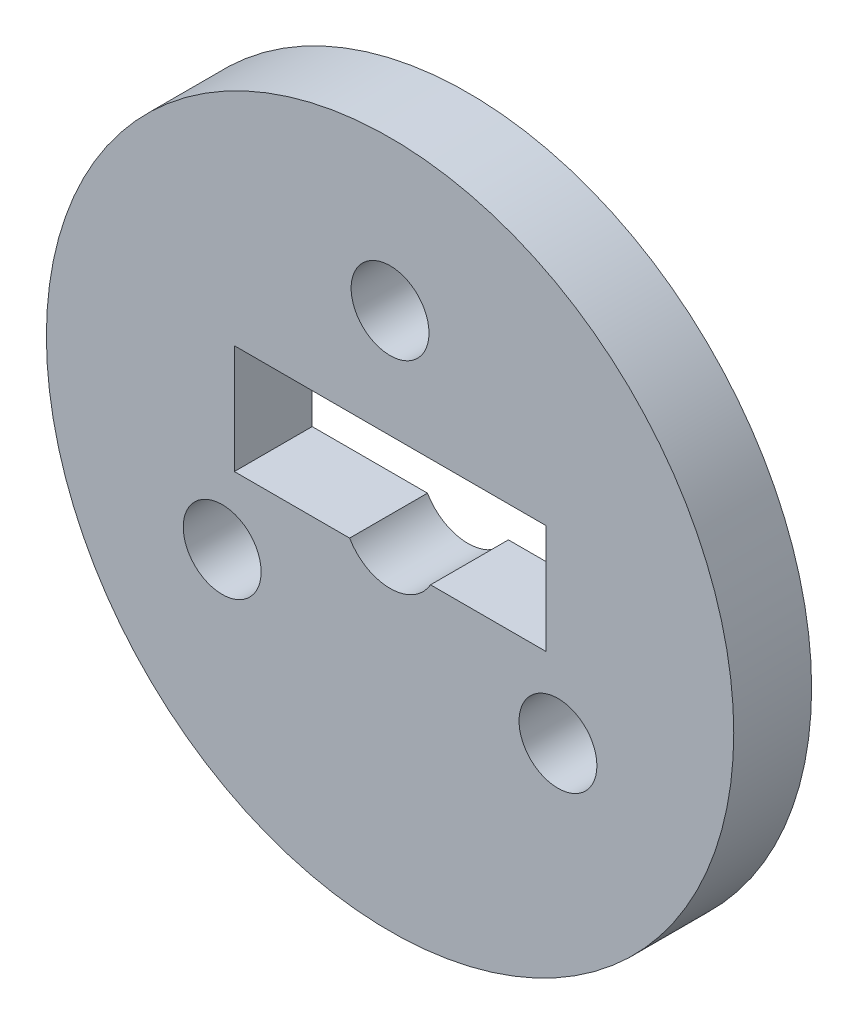
SolidWorks part; units mm, degrees
ref_plane "정면" through (0, 0, 0) normal (0, 0, 1) x (1, 0, 0)
ref_plane "윗면" through (0, 0, 0) normal (0, 1, 0) x (1, 0, 0)
ref_plane "우측면" through (0, 0, 0) normal (1, 0, 0) x (0, 0, -1)
sketch "스케치1" plane through (0, 0, 0) normal (0, 0, 1) x (1, 0, 0)
  line L0 (0, 0) -> (0, 33.5972) construction
  line L1 (0, 0) -> (0, 53.0624) construction
  line L6 (10, -1.5) -> (10, 5.5)
  line L7 (-10, 5.5) -> (-10, -1.5)
  line L8 (0, 0) -> (-11.0851, -6.4) construction
  line L9 (10, 5.5) -> (-10, 5.5)
  line L10 (10, -1.5) -> (-10, -1.5)
  line L11 (10, 5.5) -> (-10, -1.5) construction
  line L12 (10, -1.5) -> (-10, 5.5) construction
  circle A0 centre (0, 0) radius 22.0716
  circle A1 centre (0, 12.45) radius 2.5
  circle A2 centre (0, 0) radius 15.95
  circle A3 centre (10.782, -6.225) radius 2.5
  circle A4 centre (-10.782, -6.225) radius 2.5
  circle A6 centre (0, 0) radius 3
  point P0 (0, 2)
  point P14 (0, 0)
  point P22 (0, 0)
  dimension "D1" = 5
  dimension "D2" = 31.9
  dimension "D3" = 44.1433
  dimension "D4" = 12.45
  dimension "D6" = 2
  dimension "D7" = 20
  dimension "D9" = 6
  dimension "D8" = 7
  dimension "D5" = 3
extrude "보스-돌출1" add sketch "스케치1" along normal blind 5
